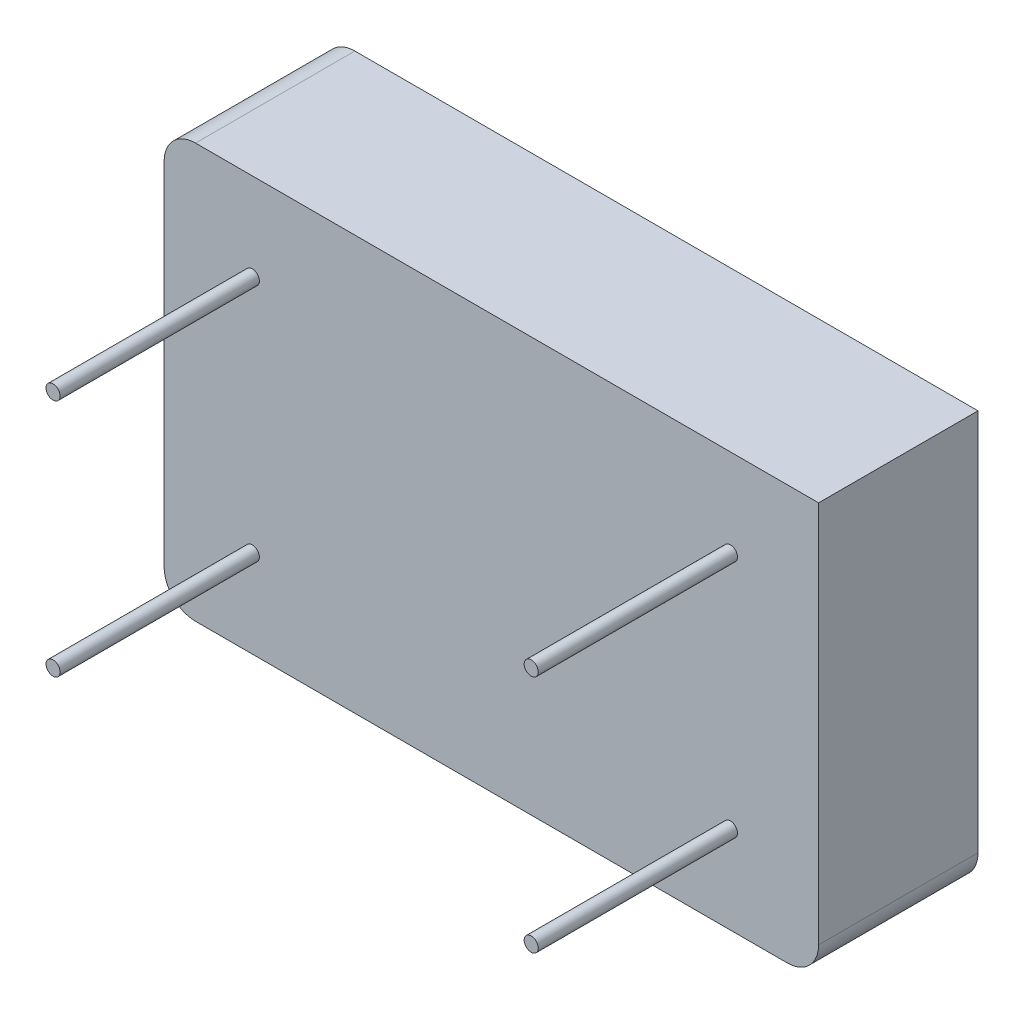
SolidWorks part; units mm, degrees
ref_plane "Front Plane" through (0, 0, 0) normal (0, 0, 1) x (1, 0, 0)
ref_plane "Top Plane" through (0, 0, 0) normal (0, 1, 0) x (1, 0, 0)
ref_plane "Right Plane" through (0, 0, 0) normal (1, 0, 0) x (0, 0, -1)
sketch "Sketch1" plane through (0, 0, 0) normal (0, 0, 1) x (1, 0, 0)
  line L0 (0, 6.6) -> (20.86, 6.6) construction
  line L1 (0, 0) -> (20.86, 0)
  line L2 (0, 0) -> (0, 13.2)
  line L3 (0, 13.2) -> (20.86, 13.2)
  line L4 (20.86, 0) -> (20.86, 13.2)
  dimension "D1" = 20.86
  dimension "D2" = 13.2
extrude "Boss-Extrude1" add sketch "Sketch1" along normal blind 5.08
sketch "Sketch2" plane through (0, 0, 5.08) normal (0, 0, 1) x (1, 0, 0)
  line L0 (0, 6.6) -> (20.86, 6.6) construction
  line L1 (0, 13.2) -> (0, 0) construction
  line L2 (20.86, 0) -> (20.86, 13.2) construction
  line L3 (10.43, 13.2) -> (10.43, 0) construction
  line L4 (20.86, 13.2) -> (0, 13.2) construction
  line L5 (0, 0) -> (20.86, 0) construction
  circle A0 centre (2.81, 10.41) radius 0.225
  circle A1 centre (18.05, 10.41) radius 0.225
  circle A2 centre (18.05, 2.79) radius 0.225
  circle A3 centre (2.81, 2.79) radius 0.225
  dimension "D1" = 0.45
  dimension "D2" = 3.81
  dimension "D3" = 7.62
extrude "Boss-Extrude2" add sketch "Sketch2" along normal blind 6.35
fillet "Fillet1" radius 1 3 edges at (0, 0, 2.54) (20.86, 0, 2.54) (0, 13.2, 2.54)
